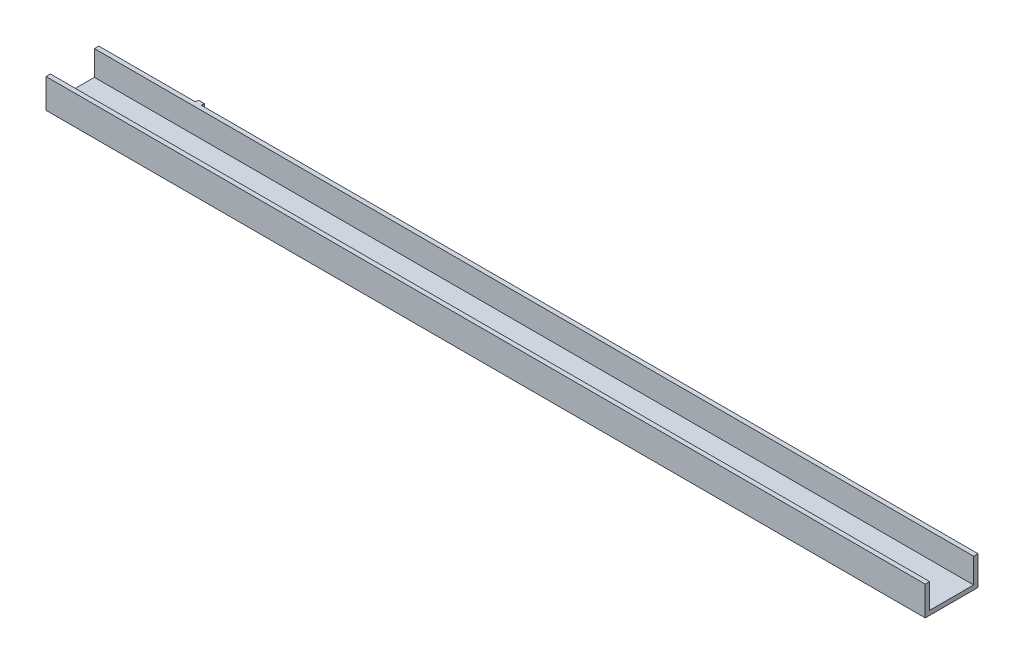
SolidWorks part; units mm, degrees
ref_plane "Front Plane" through (0, 0, 0) normal (0, 0, 1) x (1, 0, 0)
ref_plane "Top Plane" through (0, 0, 0) normal (0, 1, 0) x (1, 0, 0)
ref_plane "Right Plane" through (0, 0, 0) normal (1, 0, 0) x (0, 0, -1)
sketch "Sketch1" plane through (0, 0, 0) normal (1, 0, 0) x (0, 0, -1)
  line L0 (0, 43.9767) -> (0, -39.6063) construction
  line L1 (-83.9472, 0) -> (92.3237, 0) construction
  line L2 (-9, -6.4239) -> (9, -6.4239)
  line L3 (9, -6.4239) -> (9, 3.5761)
  line L4 (9, 3.5761) -> (7.5, 3.5761)
  line L5 (7.5, 3.5761) -> (7.5, -4.9239)
  line L6 (7.5, -4.9239) -> (-7.5, -4.9239)
  line L7 (-7.5, -4.9239) -> (-7.5, 3.5761)
  line L8 (-7.5, 3.5761) -> (-9, 3.5761)
  line L9 (-9, 3.5761) -> (-9, -6.4239)
  dimension "D1" = 18
  dimension "D2" = 1.5
  dimension "D3" = 1.5
  dimension "D4" = 1.5
  dimension "D5" = 10
extrude "Boss-Extrude1" add sketch "Sketch1" along normal blind 300
sketch "Sketch2" plane through (0, 0, -9) normal (0, 0, -1) x (-1, 0, 0)
  line L0 (-35, -6.4239) -> (-35, 3.5761)
  line L1 (-300, -6.4239) -> (0, -6.4239) construction
  line L2 (-300, 3.5761) -> (0, 3.5761) construction
  line L3 (-35, 3.5761) -> (-33, 3.5761)
  line L4 (-33, 3.5761) -> (-33, -6.4239)
  line L5 (-33, -6.4239) -> (-35, -6.4239)
  line L6 (0, -6.4239) -> (0, 3.5761) construction
  dimension "D1" = 35
  dimension "D2" = 2
extrude "Boss-Extrude2" add sketch "Sketch2" along normal blind 1
